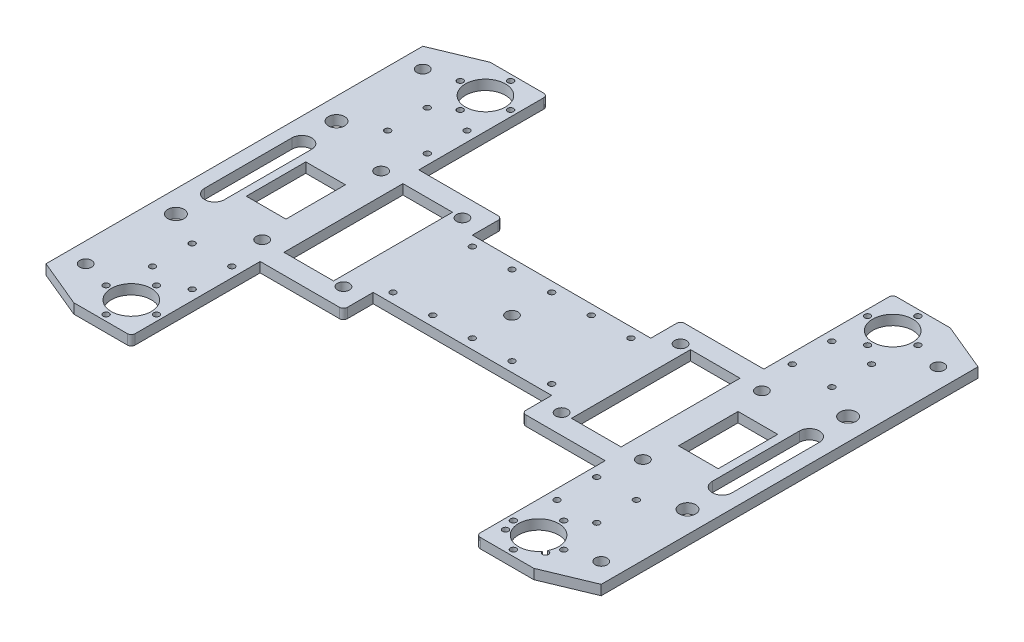
SolidWorks part; units mm, degrees
ref_plane "Plan de face" through (0, 0, 0) normal (0, 0, 1) x (1, 0, 0)
ref_plane "Plan de dessus" through (0, 0, 0) normal (0, 1, 0) x (1, 0, 0)
ref_plane "Plan de droite" through (0, 0, 0) normal (1, 0, 0) x (0, 0, -1)
sketch "Esquisse2" plane through (0, 0, 0) normal (0, 1, 0) x (1, 0, 0)
  line L0 (-140, 95) -> (-140, -95)
  line L1 (-140, 95) -> (-116, 105)
  line L2 (-116, 105) -> (-87, 105)
  line L3 (-140, -95) -> (-116, -105)
  line L4 (-116, -105) -> (-87, -105)
  line L5 (-87, 105) -> (-87, 40)
  line L6 (-87, 40) -> (-45, 40)
  line L7 (-45, 40) -> (-45, 25)
  line L8 (-45, 25) -> (45, 25)
  line L9 (0, 25) -> (0, -25) construction
  line L10 (45, -25) -> (-45, -25)
  line L11 (-45, -25) -> (-45, -40)
  line L12 (-45, -40) -> (-87, -40)
  line L13 (-87, -40) -> (-87, -105)
  line L14 (-128, 22) -> (-128, -22) construction
  line L15 (-85, 30) -> (-60, 30)
  line L16 (-85, 30) -> (-85, -30)
  line L17 (-85, -30) -> (-60, -30)
  line L18 (-60, 30) -> (-60, -30)
  line L19 (-123, 22) -> (-123, -22)
  line L20 (-133, 22) -> (-133, -22)
  line L21 (-119, 15) -> (-99, 15)
  line L22 (-119, 15) -> (-119, -15)
  line L23 (-119, -15) -> (-99, -15)
  line L24 (-99, 15) -> (-99, -15)
  line L25 (99, 15) -> (99, -15)
  line L26 (119, -15) -> (99, -15)
  line L27 (119, 15) -> (119, -15)
  line L28 (119, 15) -> (99, 15)
  line L29 (60, 30) -> (60, -30)
  line L30 (85, -30) -> (60, -30)
  line L31 (85, 30) -> (85, -30)
  line L32 (85, 30) -> (60, 30)
  line L33 (87, -40) -> (87, -105)
  line L34 (45, -40) -> (87, -40)
  line L35 (45, -25) -> (45, -40)
  line L36 (45, 40) -> (45, 25)
  line L37 (87, 40) -> (45, 40)
  line L38 (87, 105) -> (87, 40)
  line L39 (116, -105) -> (87, -105)
  line L40 (140, -95) -> (116, -105)
  line L41 (116, 105) -> (87, 105)
  line L42 (140, 95) -> (116, 105)
  line L43 (140, 95) -> (140, -95)
  line L44 (128, 22) -> (128, -22) construction
  line L45 (123, 22) -> (123, -22)
  line L46 (133, 22) -> (133, -22)
  circle A0 centre (-96, 30) radius 3
  circle A1 centre (-96, -30) radius 3
  circle A2 centre (-55, -30) radius 3
  circle A3 centre (-55, 30) radius 3
  arc A4 (-123, 22) -> (-133, 22) centre (-128, 22) ccw
  arc A5 (-133, -22) -> (-123, -22) centre (-128, -22) ccw
  circle A6 centre (-130, 85) radius 3
  circle A7 centre (-130, -85) radius 3
  circle A8 centre (-102.7, 89.3) radius 10.1
  circle A9 centre (-90, 89.3) radius 1.5
  circle A10 centre (-102.7, 102) radius 1.5
  circle A11 centre (-115.4, 89.3) radius 1.5
  circle A12 centre (-102.7, 76.6) radius 1.5
  circle A13 centre (-102.7, -89.3) radius 10.1
  circle A14 centre (-90, -89.3) radius 1.5
  circle A15 centre (-102.7, -76.6) radius 1.5
  circle A16 centre (-115.4, -89.3) radius 1.5
  circle A17 centre (-102.7, -102) radius 1.5
  circle A18 centre (102.7, -102) radius 1.5
  circle A19 centre (115.4, -89.3) radius 1.5
  circle A20 centre (102.7, -76.6) radius 1.5
  circle A21 centre (90, -89.3) radius 1.5
  circle A22 centre (102.7, -89.3) radius 10.1
  circle A23 centre (102.7, 76.6) radius 1.5
  circle A24 centre (115.4, 89.3) radius 1.5
  circle A25 centre (102.7, 102) radius 1.5
  circle A26 centre (90, 89.3) radius 1.5
  circle A27 centre (102.7, 89.3) radius 10.1
  circle A28 centre (130, -85) radius 3
  circle A29 centre (130, 85) radius 3
  circle A30 centre (55, 30) radius 3
  circle A31 centre (55, -30) radius 3
  circle A32 centre (96, -30) radius 3
  circle A33 centre (96, 30) radius 3
  arc A34 (123, 22) -> (133, 22) centre (128, 22) cw
  arc A35 (133, -22) -> (123, -22) centre (128, -22) cw
  circle A36 centre (-129, 40.5) radius 4.1
  circle A37 centre (-129, -40.5) radius 4.1
  circle A38 centre (129, -40.5) radius 4.1
  circle A39 centre (129, 40.5) radius 4.1
  circle A40 centre (0, 0) radius 3
  point P28 (-128, 0)
  point P116 (128, 0)
  dimension "D16" = 6
  dimension "D19" = 5
  dimension "D23" = 6
  dimension "D33" = 20.2
  dimension "D34" = 3
  dimension "D41" = 20.2
  dimension "D42" = 3
  dimension "D48" = 8.2
  dimension "D51" = 6
  dimension "D1" = 190
  dimension "D2" = 24
  dimension "D3" = 10
  dimension "D4" = 10
  dimension "D5" = 24
  dimension "D6" = 140
  dimension "D7" = 50
  dimension "D8" = 80
  dimension "D9" = 42
  dimension "D10" = 65
  dimension "D11" = 26
  dimension "D12" = 25
  dimension "D13" = 60
  dimension "D14" = 55
  dimension "D15" = 10
  dimension "D17" = 11
  dimension "D18" = 5
  dimension "D20" = 44
  dimension "D21" = 43
  dimension "D22" = 10
  dimension "D24" = 29
  dimension "D25" = 29
  dimension "D26" = 20
  dimension "D27" = 30
  dimension "D28" = 4
  dimension "D29" = 12.7
  dimension "D30" = 12.7
  dimension "D31" = 12.7
  dimension "D32" = 12.7
  dimension "D35" = 3
  dimension "D36" = 3
  dimension "D37" = 12.7
  dimension "D38" = 12.7
  dimension "D39" = 12.7
  dimension "D40" = 12.7
  dimension "D43" = 3
  dimension "D44" = 15
  dimension "D45" = 10
  dimension "D46" = 10
  dimension "D47" = 11
  dimension "D49" = 40.5
  dimension "D50" = 40.5
extrude "Boss.-Extru.1" add sketch "Esquisse2" along normal blind 5
fillet "Congé2" radius 2 8 edges at (-45, 2.5, -40) (45, 2.5, -40) (45, 2.5, 40) (-45, 2.5, 40) (87, 2.5, 105) (-87, 2.5, 105) (87, 2.5, -105) (-87, 2.5, -105)
hole_wizard "Diamètre du perçage Ø3.0 (3)1" positions "Esquisse4" profile "Esquisse3" hole size "Ø3.0" standard "Iso" end condition through all
sketch "Esquisse4" plane through (0, 5, 0) normal (0, 1, 0) x (1, 0, 0)
  line L0 (-87, 40) -> (-87, 103) construction
  line L1 (87, 103) -> (87, 40) construction
  circle A0 centre (-102.7, 89.3) radius 10.1 construction
  circle A1 centre (-102.7, -89.3) radius 10.1 construction
  point P0 (-92, 69.3)
  point P2 (-92, 49.3)
  point P4 (-20, 20)
  point P6 (0, 20)
  point P8 (20, 20)
  point P10 (20, -20)
  point P12 (0, -20)
  point P14 (-20, -20)
  point P16 (-92, -69.3)
  point P18 (-92, -49.3)
  point P20 (92, -69.3)
  point P22 (92, -49.3)
  point P24 (92, 69.3)
  point P26 (92, 49.3)
  point P35 (112, 69.3)
  point P37 (112, 49.3)
  point P39 (-112, 69.3)
  point P41 (-112, 49.3)
  point P43 (-112, -49.3)
  point P45 (-112, -69.3)
  point P47 (112, -69.3)
  point P49 (112, -49.3)
  point P51 (40, -20)
  point P53 (40, 20)
  point P55 (-40, 20)
  point P57 (-40, -20)
  dimension "D2" = 20
  dimension "D3" = 20
  dimension "D4" = 20
  dimension "D5" = 20
  dimension "D6" = 20
  dimension "D7" = 20
  dimension "D8" = 20
  dimension "D9" = 20
  dimension "D10" = 20
  dimension "D11" = 5
  dimension "D12" = 5
  dimension "D13" = 20
  dimension "D14" = 20
  dimension "D15" = 20
sketch "Esquisse3" plane through (-92, 5, -69.3) normal (1, 0, 0) x (0, 0, 1)
  line L0 (0, 0) -> (0, 5)
  line L1 (0, 5) -> (1.5, 5)
  line L2 (1.5, 5) -> (1.5, 0)
  line L5 (1.5, 0) -> (0, 0)
  line L11 (0, -6.35) -> (0, 107.95) construction
  dimension "Diamètre du perçage jusqu'au prochain" = 3
  dimension "Profondeur du perçage jusqu'au prochain" = 5
sketch "Esquisse6" plane through (0, 0, 0) normal (0, -1, 0) x (1, 0, 0)
  circle A0 centre (112.2187, 95.2736) radius 1.4959
  circle A1 centre (91.9957, 95.2736) radius 1.5101
extrude "Enlèv. mat.-Extru.1" cut sketch "Esquisse6" against normal blind 10
